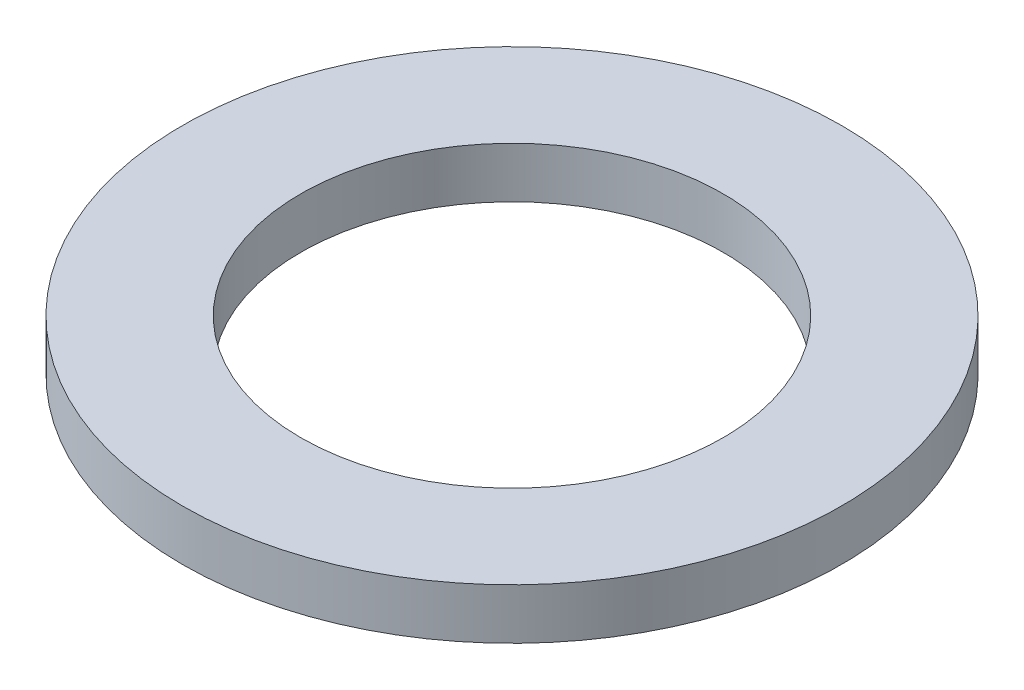
SolidWorks part; units mm, degrees
material "AISI 304"
ref_plane "前视基准面" through (0, 0, 0) normal (0, 0, 1) x (1, 0, 0)
ref_plane "上视基准面" through (0, 0, 0) normal (0, 1, 0) x (1, 0, 0)
ref_plane "右视基准面" through (0, 0, 0) normal (1, 0, 0) x (0, 0, -1)
other "Configuration Table"
sketch "草图1" plane through (0, 0, 0) normal (0, 1, 0) x (1, 0, 0)
  circle A0 centre (0, 0) radius 19.5
  circle A1 centre (0, 0) radius 12.5
  dimension "D1" = 25
  dimension "D2" = 39
extrude "凸台-拉伸1" add sketch "草图1" along normal blind 3
